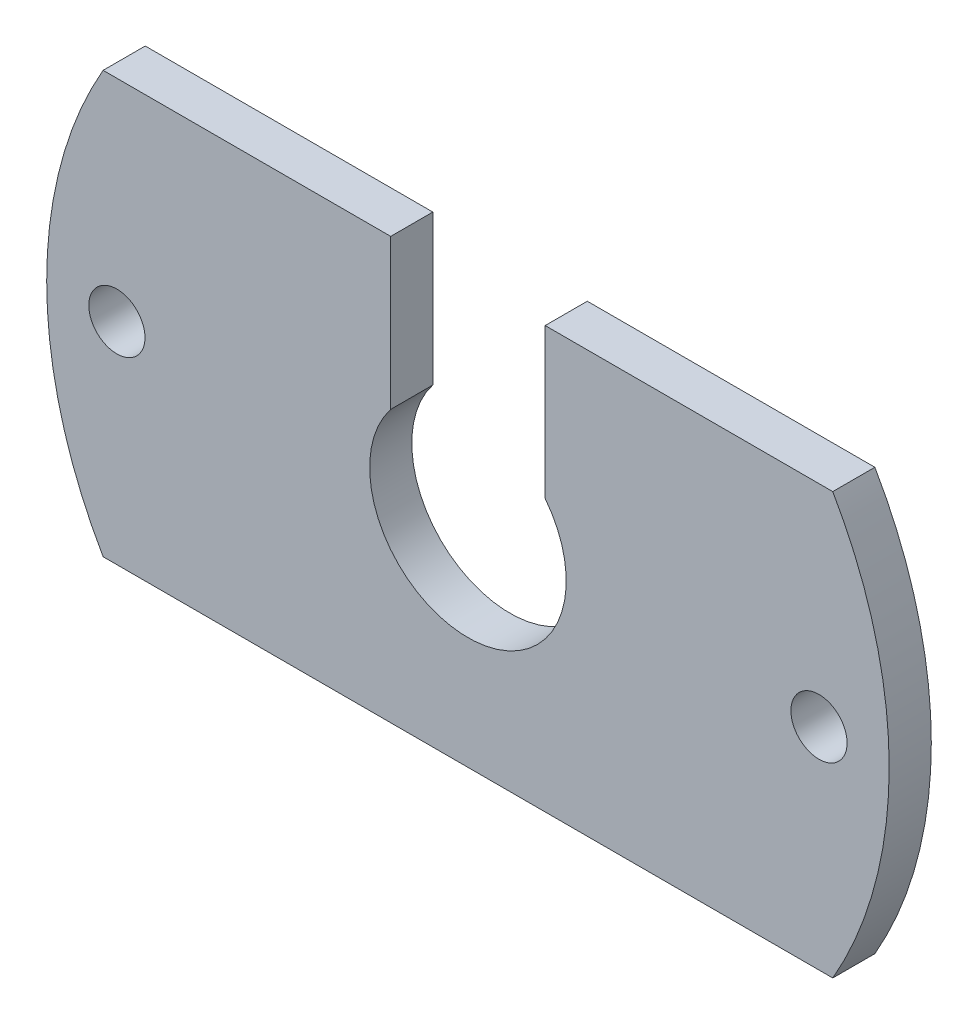
SolidWorks part; units mm, degrees
ref_plane "Plan de face" through (0, 0, 0) normal (0, 0, 1) x (1, 0, 0)
ref_plane "Plan de dessus" through (0, 0, 0) normal (0, 1, 0) x (1, 0, 0)
ref_plane "Plan de droite" through (0, 0, 0) normal (1, 0, 0) x (0, 0, -1)
sketch "Esquisse1" plane through (0, 0, 0) normal (0, 0, 1) x (1, 0, 0)
  line L0 (-5.5, 15) -> (-25.9808, 15)
  line L1 (25.9808, -15) -> (-25.9808, -15)
  line L3 (25.9808, 15) -> (5.5, 15)
  line L5 (25.9808, -15) -> (-25.9808, 15) construction
  line L6 (25.9808, 15) -> (-25.9808, -15) construction
  line L7 (5.5, 15) -> (5.5, 4.3301)
  line L8 (-5.5, 15) -> (-5.5, 4.3301)
  arc A0 (-25.9808, 15) -> (-25.9808, -15) centre (0, 0) ccw
  arc A1 (-5.5, 4.3301) -> (5.5, 4.3301) centre (0, 0) ccw
  arc A2 (25.9808, -15) -> (25.9808, 15) centre (0, 0) ccw
  circle A3 centre (-25, 0) radius 2
  circle A4 centre (25, 0) radius 2
  point P8 (0, 15)
  point P9 (0, 4.4555)
  dimension "D1" = 60
  dimension "D3" = 14
  dimension "D5" = 4
  dimension "D6" = 4
  dimension "D2" = 30
  dimension "D4" = 50
  dimension "D7" = 25
extrude "Boss.-Extru.1" add sketch "Esquisse1" along normal blind 3
